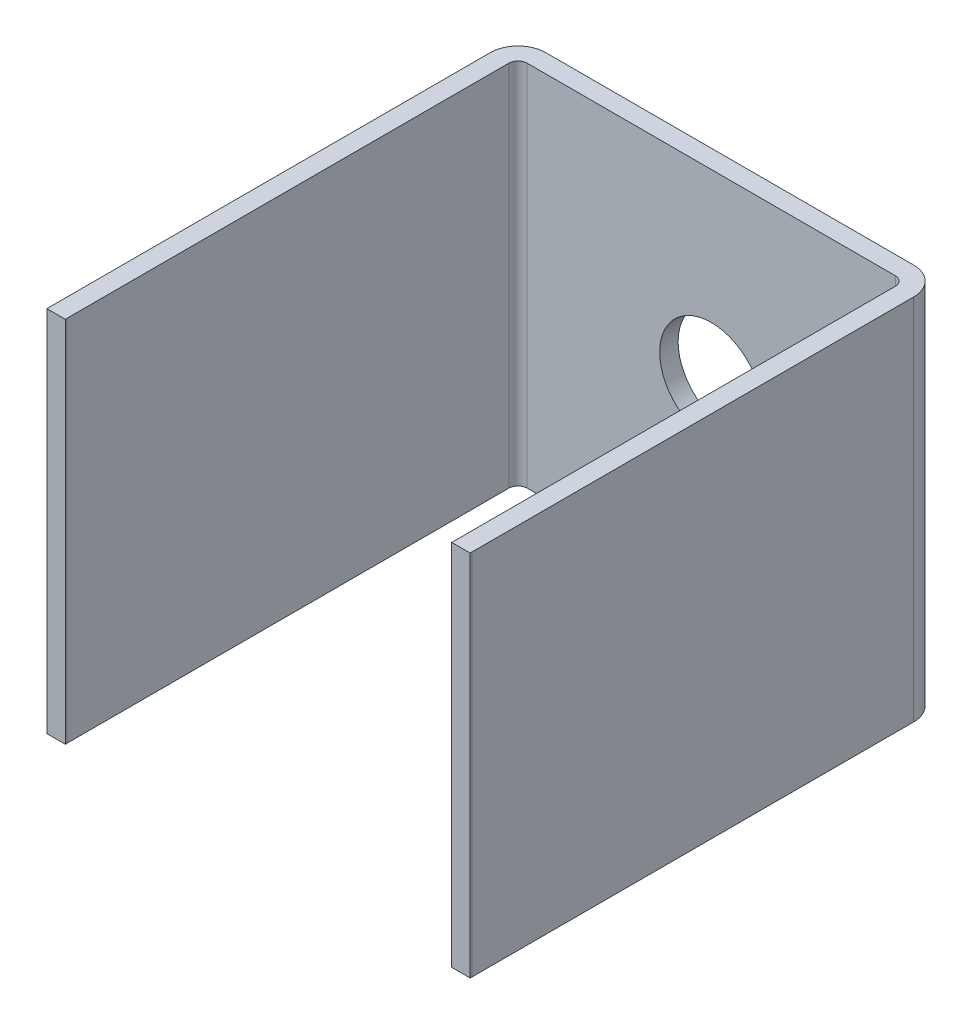
SolidWorks part; units mm, degrees
material "Plain Carbon Steel"
ref_plane "Front Plane" through (0, 0, 0) normal (0, 0, 1) x (1, 0, 0)
ref_plane "Top Plane" through (0, 0, 0) normal (0, 1, 0) x (1, 0, 0)
ref_plane "Right Plane" through (0, 0, 0) normal (1, 0, 0) x (0, 0, -1)
sketch "Sketch1" plane through (0, 0, 0) normal (0, 1, 0) x (1, 0, 0)
  line L1 (-50, -65) -> (50, -65)
  line L2 (-55, -60) -> (-55, 60)
  line L3 (-50, 65) -> (50, 65)
  line L4 (55, -60) -> (55, 60)
  arc A0 (50, 65) -> (55, 60) centre (50, 60) cw
  arc A1 (50, -65) -> (55, -60) centre (50, -60) ccw
  arc A2 (-50, -65) -> (-55, -60) centre (-50, -60) cw
  arc A3 (-55, 60) -> (-50, 65) centre (-50, 60) cw
  point P11 (-55, -65)
  point P14 (-55, 65)
  point P15 (55, 0)
  point P17 (0, -65)
  dimension "D2" = 5
  dimension "D1" = 130
  dimension "D3" = 100
extrude "Extrude-Thin1" add sketch "Sketch1" along normal mid plane 100 thin thin type mid plane wall 5
sketch "Sketch3" plane through (0, 0, -67.5) normal (0, 0, -1) x (-1, 0, 0)
  circle A0 centre (0, 0) radius 14
  dimension "D1" = 28
extrude "Cut-Extrude2" cut sketch "Sketch3" against normal blind 10
sketch "Sketch4" plane through (0, 50, 0) normal (0, 1, 0) x (1, 0, 0)
  line L0 (-50, -67.5) -> (50, -67.5) construction
  line L1 (58.4235, -79.6873) -> (-71.5351, -79.6873)
  line L2 (58.4235, -79.6873) -> (58.4235, -60.5)
  line L3 (58.4235, -60.5) -> (-71.5351, -60.5)
  line L4 (-71.5351, -79.6873) -> (-71.5351, -60.5)
  dimension "D1" = 7
extrude "Cut-Extrude3" cut sketch "Sketch4" against normal up to next contours L3 L4 L1 L2
